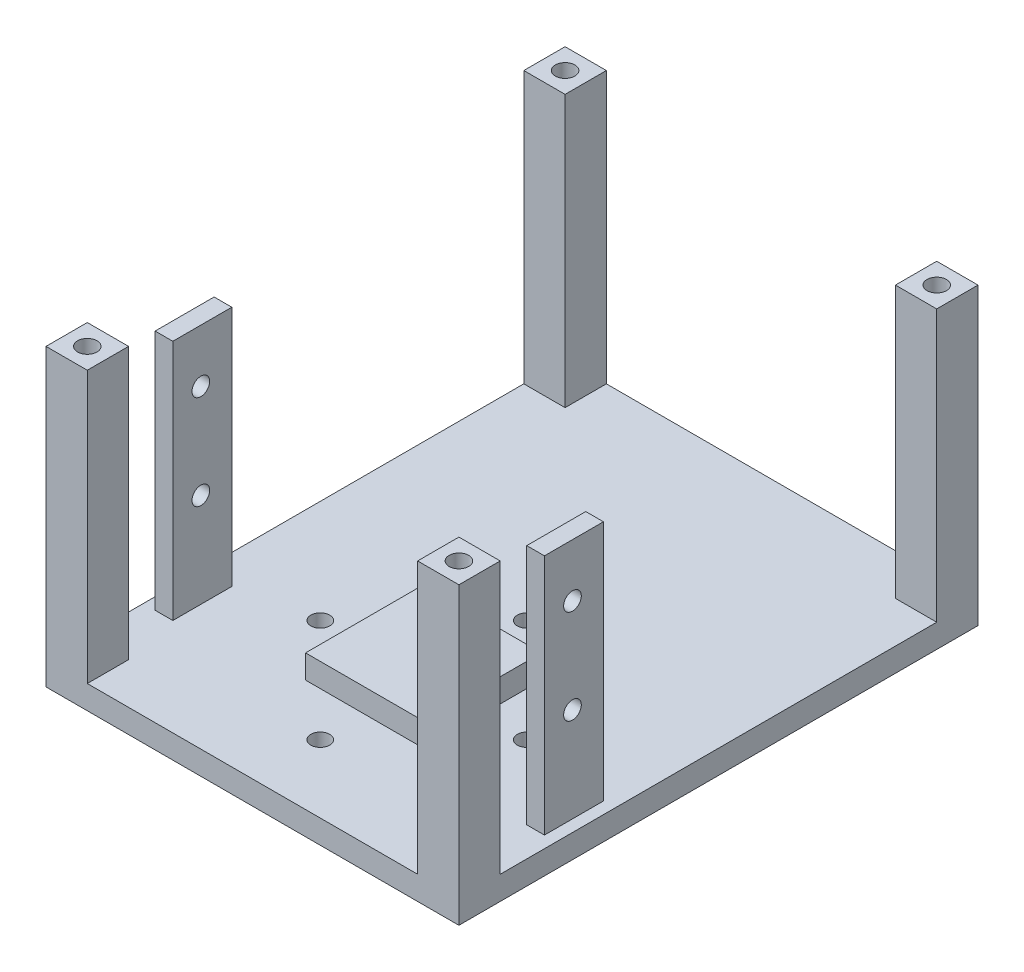
SolidWorks part; units mm, degrees
ref_plane "Front Plane" through (0, 0, 0) normal (0, 0, 1) x (1, 0, 0)
ref_plane "Top Plane" through (0, 0, 0) normal (0, 1, 0) x (1, 0, 0)
ref_plane "Right Plane" through (0, 0, 0) normal (1, 0, 0) x (0, 0, -1)
sketch "Sketch1" plane through (0, 0, 0) normal (0, 1, 0) x (1, 0, 0)
  line L1 (35, -44) -> (-35, -44)
  line L2 (35, -44) -> (35, 44)
  line L3 (35, 44) -> (-35, 44)
  line L4 (-35, -44) -> (-35, 44)
  line L5 (35, -44) -> (-35, 44) construction
  line L6 (35, 44) -> (-35, -44) construction
  point P0 (0, 0)
  dimension "D1" = 70
  dimension "D2" = 88
extrude "Boss-Extrude1" add sketch "Sketch1" along normal blind 50
sketch "Sketch2" plane through (0, 50, 0) normal (0, 1, 0) x (1, 0, 0)
  line L2 (0, 0) -> (0, 41.266) construction
  line L3 (0, 0) -> (51.8558, 0) construction
  circle A0 centre (-31.5, 40.5) radius 1.65
  circle A1 centre (31.5, 40.5) radius 1.65
  circle A2 centre (31.5, -40.5) radius 1.65
  circle A3 centre (-31.5, -40.5) radius 1.65
  dimension "D1" = 3.3
  dimension "D2" = 63
  dimension "D3" = 81
extrude "Cut-Extrude1" cut sketch "Sketch2" against normal blind 8
sketch "Sketch3" plane through (0, 50, 0) normal (0, 1, 0) x (1, 0, 0)
  line L0 (35, 44) -> (-35, 44) construction
  line L1 (-28, -44) -> (28, -44)
  line L3 (-28, 44) -> (28, 44)
  line L5 (-35, -44) -> (35, -44) construction
  line L6 (-28, 37) -> (-35, 37)
  line L7 (-35, 37) -> (-35, -37)
  line L8 (-35, -37) -> (-28, -37)
  line L9 (-35, 44) -> (-35, -44) construction
  line L10 (-28, -37) -> (-28, -44)
  line L11 (-28, 37) -> (-28, 44)
  line L12 (28, 44) -> (28, 37)
  line L13 (28, 37) -> (35, 37)
  line L14 (35, 37) -> (35, -37)
  line L15 (35, -37) -> (28, -37)
  line L16 (28, -37) -> (28, -44)
  line L17 (35, -44) -> (35, 44) construction
  circle A0 centre (-31.5, 40.5) radius 1.65 construction
  circle A2 centre (-31.5, -40.5) radius 1.65 construction
  circle A3 centre (31.5, -40.5) radius 1.65 construction
  circle A4 centre (31.5, 40.5) radius 1.65 construction
  dimension "D1" = 3.5
  dimension "D2" = 3.5
  dimension "D3" = 0
  dimension "D4" = 0
  dimension "D5" = 3.5
  dimension "D6" = 0
  dimension "D7" = 3.5
  dimension "D8" = 3.5
  dimension "D9" = 3.5
  dimension "D10" = 0
  dimension "D11" = 3.5
  dimension "D12" = 3.5
extrude "Cut-Extrude2" cut sketch "Sketch3" against normal offset from surface (46 mm away) 4 up to face at (0, 0, 0)
sketch "Sketch5" plane through (0, 4, 0) normal (0, 1, 0) x (1, 0, 0)
  line L0 (35, 37) -> (35, -37) construction
  line L1 (-28, 44) -> (28, 44) construction
  line L2 (-35, -37) -> (-35, 37) construction
  circle A0 centre (-17.5, -15) radius 1.6
  circle A1 centre (0, 2.5) radius 1.6
  circle A2 centre (0, -32.5) radius 1.6
  circle A3 centre (17.5, -15) radius 1.6
  dimension "D1" = 3.2
  dimension "D2" = 35
  dimension "D3" = 35
  dimension "D4" = 3.2
  dimension "D5" = 3.2
  dimension "D6" = 17.5
  dimension "D7" = 59
  dimension "D8" = 3.2
  dimension "D9" = 17.5
  dimension "D10" = 17.5
  dimension "D11" = 35
  dimension "D12" = 35
extrude "Cut-Extrude4" cut sketch "Sketch5" against normal through all
sketch "Sketch6" plane through (0, 4, 0) normal (0, 1, 0) x (1, 0, 0)
  line L1 (-10, -25) -> (10, -25)
  line L2 (-10, -25) -> (-10, -5)
  line L3 (-10, -5) -> (10, -5)
  line L4 (10, -25) -> (10, -5)
  circle A0 centre (0, -32.5) radius 1.6 construction
  circle A1 centre (17.5, -15) radius 1.6 construction
  dimension "D1" = 20
  dimension "D2" = 20
  dimension "D3" = 7.5
  dimension "D4" = 7.5
extrude "Boss-Extrude2" add sketch "Sketch6" along normal blind 4
sketch "Sketch7" plane through (0, 4, 0) normal (0, 1, 0) x (1, 0, 0)
  line L0 (-10, -5) -> (-10, -25) construction
  line L1 (-30, -27.5) -> (-33, -27.5)
  line L2 (-30, -27.5) -> (-30, -17.5)
  line L3 (-30, -17.5) -> (-33, -17.5)
  line L4 (-33, -27.5) -> (-33, -17.5)
  line L5 (-10, -25) -> (10, -25) construction
  line L7 (30, -27.5) -> (33, -27.5)
  line L8 (30, -27.5) -> (30, -17.5)
  line L9 (30, -17.5) -> (33, -17.5)
  line L10 (33, -27.5) -> (33, -17.5)
  line L11 (10, -25) -> (10, -5) construction
  dimension "D1" = 20
  dimension "D2" = 3
  dimension "D3" = 10
  dimension "D4" = 2.5
  dimension "D5" = 3
  dimension "D6" = 10
  dimension "D7" = 20
  dimension "D8" = 2.5
extrude "Boss-Extrude3" add sketch "Sketch7" along normal offset from surface (41 mm away) 5 up to face at (-31.5, 50, 40.5)
sketch "Sketch8" plane through (-30, 0, 0) normal (1, 0, 0) x (0, 0, -1)
  line L0 (-27.5, 45) -> (-27.5, 4) construction
  line L1 (-27.5, 4) -> (-17.5, 4) construction
  circle A0 centre (-22.75, 20) radius 1.5
  circle A1 centre (-22.75, 36) radius 1.5
  dimension "D1" = 3
  dimension "D2" = 4.75
  dimension "D3" = 16
  dimension "D4" = 3
  dimension "D5" = 16
  dimension "D6" = 4.75
extrude "Cut-Extrude5" cut sketch "Sketch8" against normal blind 10
sketch "Sketch9" plane through (30, 0, 0) normal (-1, 0, 0) x (0, 0, 1)
  line L0 (27.5, 45) -> (27.5, 4) construction
  line L1 (17.5, 4) -> (27.5, 4) construction
  circle A0 centre (22.75, 20) radius 1.5
  circle A1 centre (22.75, 36) radius 1.5
  dimension "D1" = 3
  dimension "D2" = 4.75
  dimension "D3" = 16
  dimension "D4" = 3
  dimension "D5" = 16
  dimension "D6" = 4.75
extrude "Cut-Extrude6" cut sketch "Sketch9" against normal blind 10
